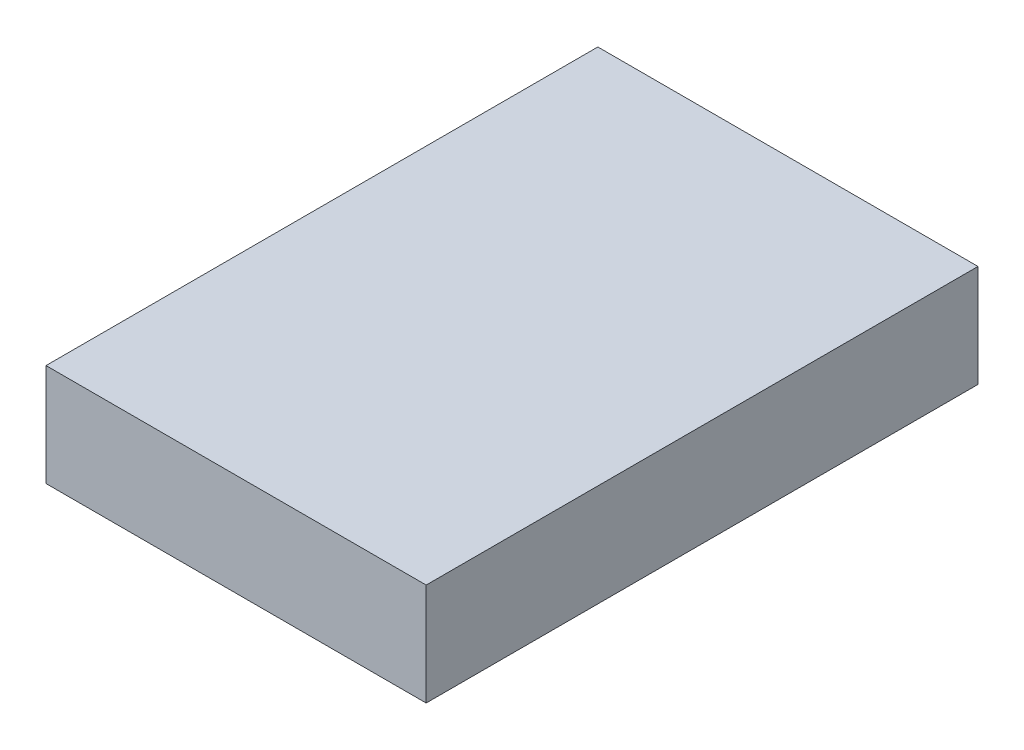
SolidWorks part; units mm, degrees
ref_plane "Front Plane" through (0, 0, 0) normal (0, 0, 1) x (1, 0, 0)
ref_plane "Top Plane" through (0, 0, 0) normal (0, 1, 0) x (1, 0, 0)
ref_plane "Right Plane" through (0, 0, 0) normal (1, 0, 0) x (0, 0, -1)
sketch "Sketch1" plane through (0, 0, 0) normal (0, 1, 0) x (1, 0, 0)
  line L1 (0, 0) -> (7.44, 0)
  line L2 (0, 0) -> (0, 10.8)
  line L3 (0, 10.8) -> (7.44, 10.8)
  line L4 (7.44, 0) -> (7.44, 10.8)
  dimension "D1" = 7.44
  dimension "D2" = 10.8
extrude "Boss-Extrude1" add sketch "Sketch1" along normal blind 2
